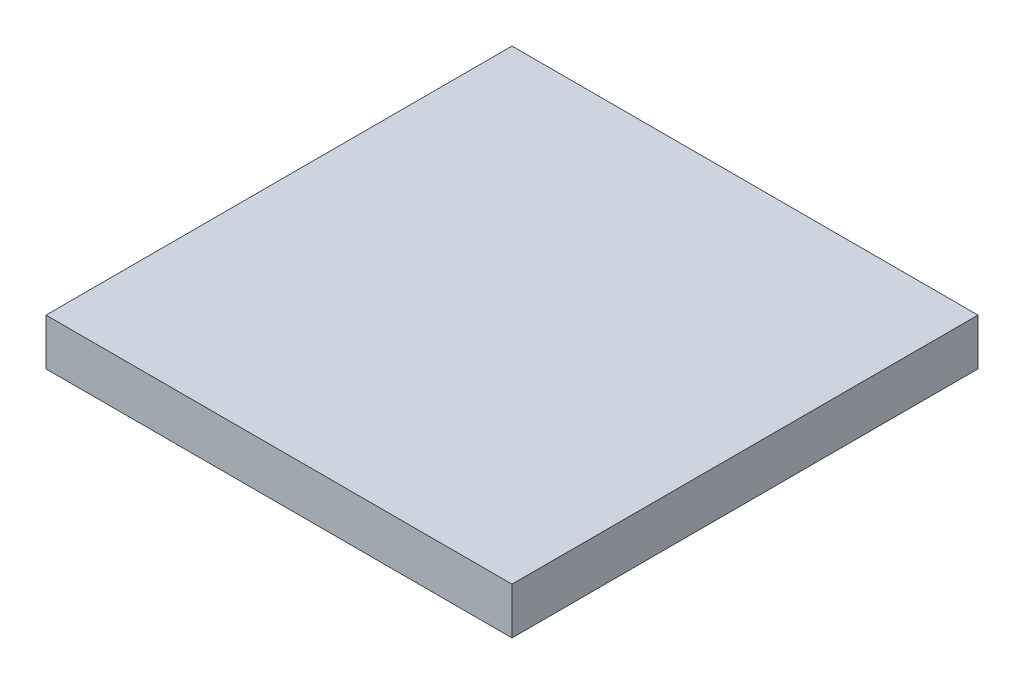
SolidWorks part; units mm, degrees
ref_plane "前视基准面" through (0, 0, 0) normal (0, 0, 1) x (1, 0, 0)
ref_plane "上视基准面" through (0, 0, 0) normal (0, 1, 0) x (1, 0, 0)
ref_plane "右视基准面" through (0, 0, 0) normal (1, 0, 0) x (0, 0, -1)
other "Configuration Table"
sketch "草图1" plane through (0, 0, 0) normal (0, 0, 1) x (1, 0, 0)
  line L0 (-5, 0) -> (5, 0)
extrude "Thin_2_0.001" add sketch "草图1" along normal blind 10 thin thin type mid plane wall 1
